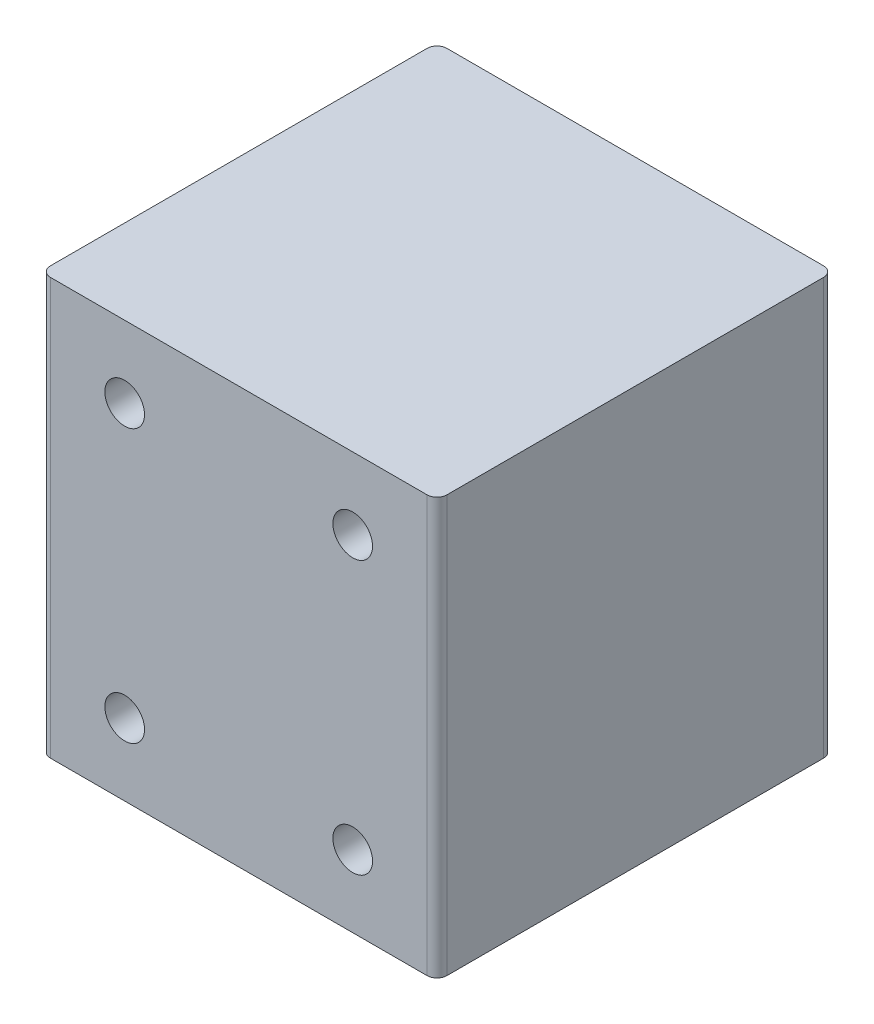
SolidWorks part; units mm, degrees
material "1.4000 (X6Cr13)"
ref_plane "Płaszczyzna przednia" through (0, 0, 0) normal (0, 0, 1) x (1, 0, 0)
ref_plane "Płaszczyzna górna" through (0, 0, 0) normal (0, 1, 0) x (1, 0, 0)
ref_plane "Płaszczyzna prawa" through (0, 0, 0) normal (1, 0, 0) x (0, 0, -1)
sketch "Szkic1" plane through (0, 0, 0) normal (0, 1, 0) x (1, 0, 0)
  line L1 (-40, -40) -> (40, -40)
  line L2 (-40, -40) -> (-40, 40)
  line L3 (-40, 40) -> (40, 40)
  line L4 (40, -40) -> (40, 40)
  line L5 (-40, -40) -> (40, 40) construction
  line L6 (-40, 40) -> (40, -40) construction
  point P0 (0, 0)
  dimension "D1" = 80
  dimension "D2" = 80
extrude "Dodanie-wyciągnięcie1" add sketch "Szkic1" along normal blind 84
sketch "Szkic2" plane through (0, 0, 40) normal (0, 0, 1) x (1, 0, 0)
  line L0 (0, 96.0642) -> (0, -19.6551) construction
  line L1 (-52.1243, 42) -> (61.0647, 42) construction
  line L2 (40, 84) -> (40, 0) construction
  circle A0 centre (-23, 69.5) radius 4
  circle A1 centre (23, 69.5) radius 4
  circle A2 centre (23, 14.5) radius 4
  circle A3 centre (-23, 14.5) radius 4
  point P7 (40, 42)
  dimension "D1" = 8
  dimension "D2" = 46
  dimension "D3" = 55
hole_wizard "Otwory ustalające Ø8.0mm1" positions "Szkic3" profile "Szkic4" hole size "Ø8.0" standard "ISO"
sketch "Szkic3" plane through (0, 0, 40) normal (0, 0, 1) x (1, 0, 0)
  point P0 (-23, 69.5)
  point P3 (23, 69.5)
  point P6 (23, 14.5)
  point P9 (-23, 14.5)
sketch "Szkic4" plane through (-23, 69.5, 40) normal (1, 0, 0) x (0, -1, 0)
  line L0 (0, 0) -> (0, 14.4034)
  line L1 (0, 14.4034) -> (4, 12)
  line L2 (4, 12) -> (4, 0)
  line L5 (4, 0) -> (0, 0)
  line L10 (0, 14.4034) -> (-4, 12) construction
  line L11 (0, -6.35) -> (0, 107.95) construction
  dimension "Średnica otworu" = 8
  dimension "Głębokość otworu" = 12
  dimension "Kąt wiertła" = 118
mirror "Lustro1" about plane through (0, 0, 0) normal (0, 0, 1) of "Otwory ustalające Ø8.0mm1"
fillet "Zaokrąglenie2" radius 2 4 edges at (40, 42, -40) (-40, 42, -40) (40, 42, 40) (-40, 42, 40)
